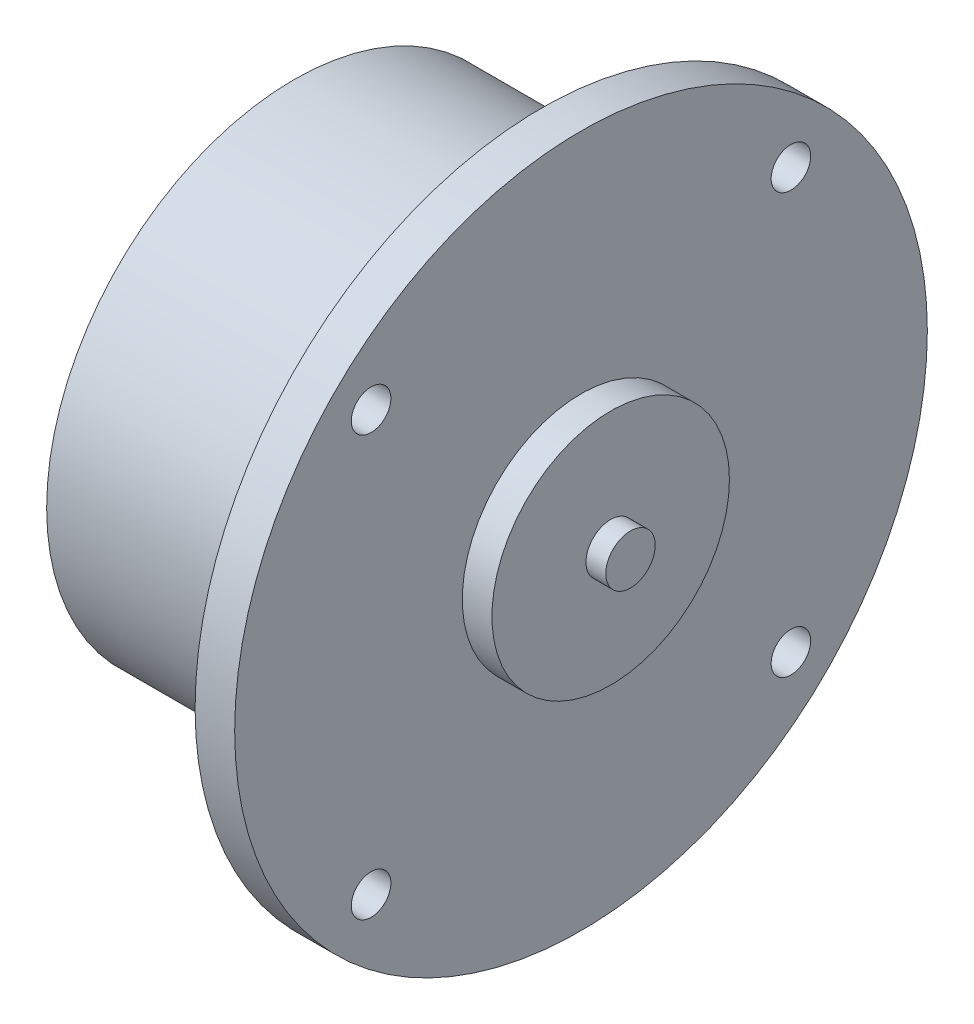
SolidWorks part; units mm, degrees
ref_plane "前视基准面" through (0, 0, 0) normal (0, 0, 1) x (1, 0, 0)
ref_plane "上视基准面" through (0, 0, 0) normal (0, 1, 0) x (1, 0, 0)
ref_plane "右视基准面" through (0, 0, 0) normal (1, 0, 0) x (0, 0, -1)
sketch "草图1" plane through (0, 0, 0) normal (1, 0, 0) x (0, 0, -1)
  line L0 (0, 35) -> (0, -35) construction
  line L1 (-35, 0) -> (35, 0) construction
  line L2 (21.2132, 21.2132) -> (-21.2132, -21.2132) construction
  line L3 (-21.2132, 21.2132) -> (21.2132, -21.2132) construction
  circle A0 centre (0, 0) radius 35
  circle A1 centre (0, 0) radius 30 construction
  circle A2 centre (21.2132, 21.2132) radius 2
  circle A3 centre (-21.2132, 21.2132) radius 2
  circle A4 centre (-21.2132, -21.2132) radius 2
  circle A5 centre (21.2132, -21.2132) radius 2
  dimension "D1" = 70
  dimension "D2" = 60
  dimension "D5" = 4
  dimension "D6" = 4
  dimension "D7" = 4
  dimension "D8" = 4
  dimension "D3" = 45
  dimension "D4" = 45
extrude "凸台-拉伸1" add sketch "草图1" along normal blind 4
sketch "草图2" plane through (4, 0, 0) normal (1, 0, 0) x (0, 0, -1)
  circle A0 centre (0, 0) radius 12
  dimension "D1" = 24
extrude "凸台-拉伸2" add sketch "草图2" along normal blind 3
sketch "草图3" plane through (7, 0, 0) normal (1, 0, 0) x (0, 0, -1)
  circle A0 centre (0, 0) radius 2.5
  dimension "D1" = 5
extrude "凸台-拉伸3" add sketch "草图3" along normal blind 2
sketch "草图4" plane through (0, 0, 0) normal (-1, 0, 0) x (0, 0, 1)
  circle A0 centre (0, 0) radius 25
  dimension "D1" = 50
extrude "凸台-拉伸4" add sketch "草图4" along normal blind 25
sketch "草图5" plane through (-25, 0, 0) normal (-1, 0, 0) x (0, 0, 1)
  circle A0 centre (0, 0) radius 2.5
  dimension "D1" = 5
extrude "凸台-拉伸5" add sketch "草图5" along normal blind 11
sketch "草图6" plane through (-36, 0, 0) normal (-1, 0, 0) x (0, 0, 1)
  line L0 (1.5, -2) -> (-1.5, -2)
  line L1 (-1.5, -2) -> (-1.5, -3.8393)
  line L2 (-1.5, -3.8393) -> (2.0419, -3.8393)
  line L3 (2.0419, -3.8393) -> (1.5, -2)
  circle A0 centre (0, 0) radius 2.5 construction
  dimension "D1" = 2
extrude "切除-拉伸1" cut sketch "草图6" against normal blind 11
